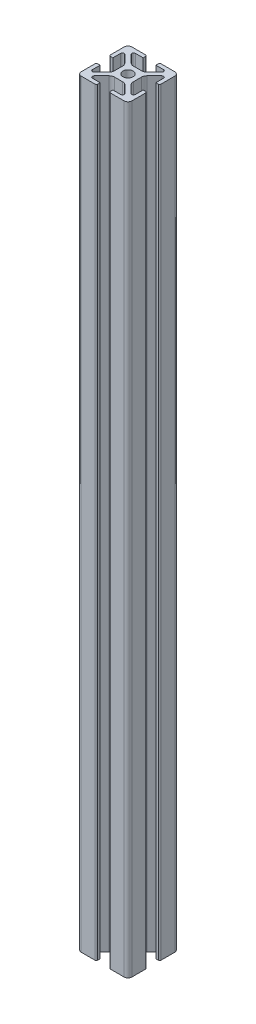
SolidWorks part; units mm, degrees
ref_plane "Plan de face" through (0, 0, 0) normal (0, 0, 1) x (1, 0, 0)
ref_plane "Plan de dessus" through (0, 0, 0) normal (0, 1, 0) x (1, 0, 0)
ref_plane "Plan de droite" through (0, 0, 0) normal (1, 0, 0) x (0, 0, -1)
sketch "Esquisse1" plane through (0, 0, 0) normal (0, 1, 0) x (1, 0, 0)
  line L0 (-5.6497, 11.1927) -> (14.3503, 11.1927) construction
  line L1 (14.3503, 11.1927) -> (14.3503, -8.8073) construction
  line L2 (14.3503, -8.8073) -> (-5.6497, -8.8073) construction
  line L3 (-5.6497, -8.8073) -> (-5.6497, 11.1927) construction
  line L4 (-5.6497, 11.1927) -> (14.3503, -8.8073) construction
  line L5 (-5.6497, -8.8073) -> (14.3503, 11.1927) construction
  line L6 (-5.6497, 9.6927) -> (-5.6497, 4.1927)
  line L7 (-5.1497, 3.6927) -> (-4.1497, 3.6927)
  line L8 (-4.1497, 3.6927) -> (-4.1497, 6.7528)
  line L9 (-2.9547, 7.2478) -> (0.0145, 4.2785)
  line L10 (0.6003, 2.8643) -> (0.6003, -0.4788)
  line L11 (0.0145, -1.8931) -> (-2.9547, -4.8623)
  line L12 (-4.1497, -4.3673) -> (-4.1497, -1.3073)
  line L13 (-4.1497, -1.3073) -> (-5.1497, -1.3073)
  line L14 (-5.6497, -1.8073) -> (-5.6497, -7.3073)
  line L15 (-4.1497, -8.8073) -> (1.3503, -8.8073)
  line L16 (1.8503, -8.3073) -> (1.8503, -7.3073)
  line L17 (1.8503, -7.3073) -> (-1.2098, -7.3073)
  line L18 (-1.7047, -6.1123) -> (1.2645, -3.1431)
  line L19 (2.6787, -2.5573) -> (6.0219, -2.5573)
  line L20 (7.4361, -3.1431) -> (10.4053, -6.1123)
  line L21 (9.9103, -7.3073) -> (6.8503, -7.3073)
  line L22 (6.8503, -7.3073) -> (6.8503, -8.3073)
  line L23 (7.3503, -8.8073) -> (12.8503, -8.8073)
  line L24 (14.3503, -7.3073) -> (14.3503, -1.8073)
  line L25 (13.8503, -1.3073) -> (12.8503, -1.3073)
  line L26 (12.8503, -1.3073) -> (12.8503, -4.3673)
  line L27 (11.6553, -4.8623) -> (8.6861, -1.8931)
  line L28 (8.1003, -0.4788) -> (8.1003, 2.8643)
  line L29 (8.6861, 4.2785) -> (11.6553, 7.2478)
  line L30 (12.8503, 6.7528) -> (12.8503, 3.6927)
  line L31 (12.8503, 3.6927) -> (13.8503, 3.6927)
  line L32 (14.3503, 4.1927) -> (14.3503, 9.6927)
  line L33 (12.8503, 11.1927) -> (7.3503, 11.1927)
  line L34 (6.8503, 10.6927) -> (6.8503, 9.6927)
  line L35 (6.8503, 9.6927) -> (9.9103, 9.6927)
  line L36 (10.4053, 8.4978) -> (7.4361, 5.5285)
  line L37 (6.0219, 4.9427) -> (2.6787, 4.9427)
  line L38 (1.2645, 5.5285) -> (-1.7047, 8.4978)
  line L39 (-1.2098, 9.6927) -> (1.8503, 9.6927)
  line L40 (1.8503, 9.6927) -> (1.8503, 10.6927)
  line L41 (1.3503, 11.1927) -> (-4.1497, 11.1927)
  line L42 (-4.1497, -6.0573) -> (-2.8997, -7.3073) construction
  line L43 (0.6003, -1.3073) -> (1.8503, -2.5573) construction
  line L44 (0.6003, 3.6927) -> (1.8503, 4.9427) construction
  line L45 (-4.1497, 8.4427) -> (-2.8997, 9.6927) construction
  line L46 (12.8503, 8.4427) -> (11.6003, 9.6927) construction
  line L47 (8.1003, 3.6927) -> (6.8503, 4.9427) construction
  line L48 (12.8503, -6.0573) -> (11.6003, -7.3073) construction
  line L49 (8.1003, -1.3073) -> (6.8503, -2.5573) construction
  line L50 (8.1003, 1.1927) -> (0.6003, 1.1927) construction
  line L51 (0.6003, 1.1927) -> (4.3503, 4.9427) construction
  line L52 (4.3503, 4.9427) -> (4.3503, -2.5573) construction
  arc A0 (14.3503, 9.6927) -> (12.8503, 11.1927) centre (12.8503, 9.6927) ccw
  arc A1 (12.8503, -8.8073) -> (14.3503, -7.3073) centre (12.8503, -7.3073) ccw
  arc A2 (-5.6497, -7.3073) -> (-4.1497, -8.8073) centre (-4.1497, -7.3073) ccw
  arc A3 (-5.6497, 9.6927) -> (-4.1497, 11.1927) centre (-4.1497, 9.6927) cw
  arc A4 (-2.9547, -4.8623) -> (-4.1497, -4.3673) centre (-3.4497, -4.3673) cw
  arc A5 (-1.2098, -7.3073) -> (-1.7047, -6.1123) centre (-1.2098, -6.6073) cw
  arc A6 (10.4053, -6.1123) -> (9.9103, -7.3073) centre (9.9103, -6.6073) cw
  arc A7 (12.8503, -4.3673) -> (11.6553, -4.8623) centre (12.1503, -4.3673) cw
  arc A8 (11.6553, 7.2478) -> (12.8503, 6.7528) centre (12.1503, 6.7528) cw
  arc A9 (9.9103, 9.6927) -> (10.4053, 8.4978) centre (9.9103, 8.9927) cw
  arc A10 (-1.7047, 8.4978) -> (-1.2098, 9.6927) centre (-1.2098, 8.9927) cw
  arc A11 (-4.1497, 6.7528) -> (-2.9547, 7.2478) centre (-3.4497, 6.7528) cw
  arc A12 (14.3503, -1.8073) -> (13.8503, -1.3073) centre (13.8503, -1.8073) ccw
  arc A13 (13.8503, 3.6927) -> (14.3503, 4.1927) centre (13.8503, 4.1927) ccw
  arc A14 (7.3503, 11.1927) -> (6.8503, 10.6927) centre (7.3503, 10.6927) ccw
  arc A15 (1.8503, 10.6927) -> (1.3503, 11.1927) centre (1.3503, 10.6927) ccw
  arc A16 (-5.6497, 4.1927) -> (-5.1497, 3.6927) centre (-5.1497, 4.1927) ccw
  arc A17 (-5.1497, -1.3073) -> (-5.6497, -1.8073) centre (-5.1497, -1.8073) ccw
  arc A18 (1.3503, -8.8073) -> (1.8503, -8.3073) centre (1.3503, -8.3073) ccw
  arc A19 (6.8503, -8.3073) -> (7.3503, -8.8073) centre (7.3503, -8.3073) ccw
  arc A20 (6.0219, -2.5573) -> (7.4361, -3.1431) centre (6.0219, -4.5573) cw
  arc A21 (0.0145, 4.2785) -> (0.6003, 2.8643) centre (-1.3997, 2.8643) cw
  arc A22 (0.6003, -0.4788) -> (0.0145, -1.8931) centre (-1.3997, -0.4788) cw
  arc A23 (1.2645, -3.1431) -> (2.6787, -2.5573) centre (2.6787, -4.5573) cw
  arc A24 (8.1003, 2.8643) -> (8.6861, 4.2785) centre (10.1003, 2.8643) cw
  arc A25 (8.6861, -1.8931) -> (8.1003, -0.4788) centre (10.1003, -0.4788) cw
  arc A26 (7.4361, 5.5285) -> (6.0219, 4.9427) centre (6.0219, 6.9427) cw
  arc A27 (2.6787, 4.9427) -> (1.2645, 5.5285) centre (2.6787, 6.9427) cw
  circle A28 centre (4.3503, 1.1927) radius 2
  point P125 (14.3503, -1.3073)
  point P128 (14.3503, 3.6927)
  point P131 (6.8503, 11.1927)
  point P134 (1.8503, 11.1927)
  point P137 (-5.6497, 3.6927)
  point P140 (-5.6497, -1.3073)
  point P143 (1.8503, -8.8073)
  point P146 (6.8503, -8.8073)
  dimension "D33" = 1.5
  dimension "D34" = 0.7
  dimension "D35" = 0.5
  dimension "D36" = 2
  dimension "D1" = 20
  dimension "D2" = 20
  dimension "D3" = 7.5
  dimension "D4" = 7.5
  dimension "7.5" = 7.5
  dimension "D5" = 7.5
  dimension "D6" = 7.5
  dimension "D7" = 7.5
  dimension "D8" = 7.5
  dimension "D9" = 7.5
  dimension "D10" = 7.5
  dimension "D11" = 7.5
  dimension "D12" = 270
  dimension "D13" = 5
  dimension "D14" = 5
  dimension "D15" = 5
  dimension "D16" = 5
  dimension "D17" = 90
  dimension "D18" = 90
  dimension "D19" = 1.5
  dimension "D20" = 135
  dimension "D21" = 1.5
  dimension "D22" = 135
  dimension "D23" = 1.5
  dimension "D24" = 1.5
  dimension "D25" = 1.5
  dimension "D26" = 1.5
  dimension "D27" = 1.5
  dimension "D28" = 90
  dimension "D29" = 90
  dimension "D30" = 90
  dimension "D31" = 90
  dimension "D32" = 90
extrude "Boss.-Extru.1" add sketch "Esquisse1" along normal blind 300
